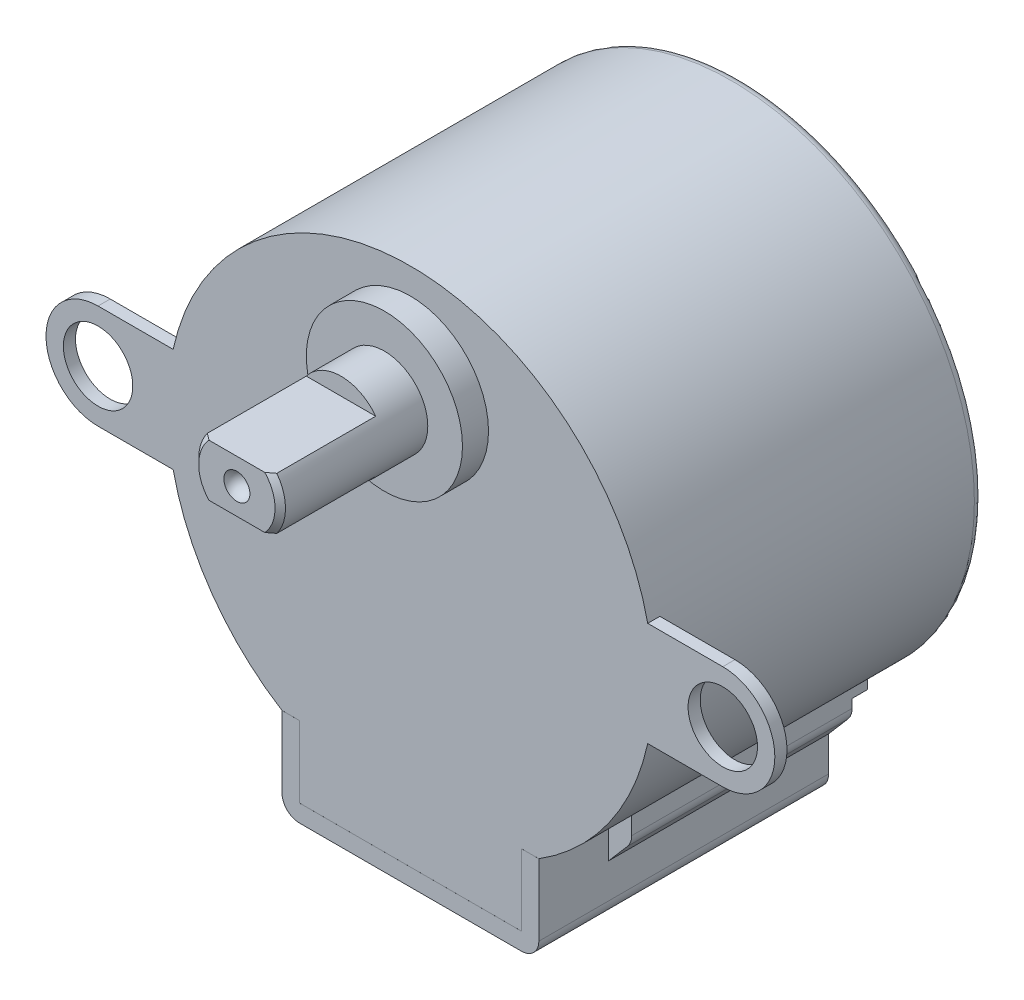
SolidWorks part; units mm, degrees
ref_plane "Ön Düzlem" through (0, 0, 0) normal (0, 0, 1) x (1, 0, 0)
ref_plane "Üst Düzlem" through (0, 0, 0) normal (0, 1, 0) x (1, 0, 0)
ref_plane "Sağ Düzlem" through (0, 0, 0) normal (1, 0, 0) x (0, 0, -1)
sketch "Çizim1" plane through (0, 0, 0) normal (0, 0, 1) x (1, 0, 0)
  circle A0 centre (0, 0) radius 14
  dimension "D1" = 28
extrude "Yükseklik-Ekstrüzyon1" add sketch "Çizim1" along normal blind 19
sketch "Çizim2" plane through (0, 0, 19) normal (0, 0, 1) x (1, 0, 0)
  line L0 (0, 14) -> (0, 8) construction
  circle A0 centre (0, 0) radius 14 construction
  circle A1 centre (0, 8) radius 4.5
  dimension "D2" = 9
  dimension "D1" = 6
extrude "Yükseklik-Ekstrüzyon2" add sketch "Çizim2" along normal blind 1.5
sketch "Çizim3" plane through (0, 0, 20.5) normal (0, 0, 1) x (1, 0, 0)
  circle A0 centre (0, 8) radius 2.5
  dimension "D1" = 5
extrude "Yükseklik-Ekstrüzyon3" add sketch "Çizim3" along normal blind 8.5
sketch "Çizim4" plane through (0, 0, 29) normal (0, 0, 1) x (1, 0, 0)
  line L0 (0, 10.5) -> (0, 9.5) construction
  line L1 (0, 9.5) -> (2.1768, 9.5)
  line L2 (2.1768, 9.5) -> (2.1768, 10.5)
  line L3 (2.1768, 10.5) -> (-2.3997, 10.5)
  line L4 (-2.3997, 10.5) -> (-2.3997, 9.5)
  line L5 (-2.3997, 9.5) -> (0, 9.5)
  line L6 (0, 8) -> (1.2994, 8) construction
  line L7 (2.1768, 5.5) -> (-2.3997, 5.5)
  line L8 (2.1768, 6.5) -> (2.1768, 5.5)
  line L9 (-2.3997, 5.5) -> (-2.3997, 6.5)
  line L10 (-2.3997, 6.5) -> (0, 6.5)
  line L11 (0, 6.5) -> (2.1768, 6.5)
  circle A0 centre (0, 8) radius 2.5 construction
  circle A1 centre (0, 8) radius 2.5 construction
  dimension "D1" = 1
extrude "Kes-Ekstrüzyon1" cut sketch "Çizim4" against normal blind 6
chamfer "Pah1" distance 0.3 angle 45 2 edges at (-2.5, 8, 29) (2.5, 8, 29)
sketch "Çizim5" plane through (0, 0, 29) normal (0, 0, 1) x (1, 0, 0)
  line L0 (0, 8.75) -> (0, 7.25) construction
  line L1 (0, 8.75) -> (0, 7.25)
  arc A0 (0, 7.25) -> (0, 8.75) centre (0, 8) ccw
  dimension "D1" = 1.5
revolve "Kes-Döndür1" cut sketch "Çizim5" angle 360 about L0
sketch "Çizim6" plane through (0, 0, 19) normal (0, 0, 1) x (1, 0, 0)
  line L0 (0, 0) -> (0, -17) construction
  line L1 (0, -17) -> (7.4, -17)
  line L2 (7.4, -17) -> (7.4, -11.8844)
  line L4 (-7.4, -11.8844) -> (-7.4, -17)
  line L5 (-7.4, -17) -> (0, -17)
  arc A0 (-7.4, -11.8844) -> (7.4, -11.8844) centre (0, 0) ccw
  dimension "D1" = 17
  dimension "D2" = 7.4
  dimension "D3" = 7.4
extrude "Yükseklik-Ekstrüzyon4" add sketch "Çizim6" against normal blind 16.7
fillet "Radyus2" radius 1 2 edges at (7.4, -17, 10.65) (-7.4, -17, 10.65)
sketch "Çizim7" plane through (0, 0, 2.3) normal (0, 0, -1) x (-1, 0, 0)
  line L0 (7.4, -14) -> (7.4, -10.9287)
  line L1 (7.4, -11.8844) -> (7.4, -16) construction
  line L2 (7.4, -14) -> (8.75, -14) construction
  line L3 (8.75, -10.9287) -> (8.75, -12.0582)
  line L4 (7.4, -14) -> (8.5085, -12.7098)
  line L5 (7.4, -10.9287) -> (8.75, -10.9287)
  line L6 (0, -17) -> (0, -15.0954) construction
  line L7 (6.4, -17) -> (-6.4, -17) construction
  line L8 (-7.4, -14) -> (-7.4, -10.9287)
  line L9 (-7.4, -10.9287) -> (-8.75, -10.9287)
  line L10 (-8.75, -10.9287) -> (-8.75, -12.0582)
  line L11 (-7.4, -14) -> (-8.5085, -12.7098)
  circle A1 centre (0, 0) radius 14 construction
  arc A2 (8.75, -12.0582) -> (8.5085, -12.7098) centre (7.75, -12.0582) cw
  arc A3 (-8.75, -12.0582) -> (-8.5085, -12.7098) centre (-7.75, -12.0582) ccw
  point P21 (8.75, -12.4287)
  point P24 (-8.75, -12.4287)
  dimension "D1" = 1
  dimension "D2" = 1.35
  dimension "D3" = 1.5
extrude "Yükseklik-Ekstrüzyon5" add sketch "Çizim7" against normal blind 12.7
sketch "Çizim8" plane through (0, 0, 2.3) normal (0, 0, -1) x (-1, 0, 0)
  line L0 (-8.75, -10.9287) -> (-8.75, -11.5623)
  line L1 (8.75, -10.9287) -> (8.75, -11.5623)
  line L4 (1.5, -14.4222) -> (1.5, -13.9194)
  line L5 (-1.5, -14.4222) -> (-1.5, -13.9194)
  arc A0 (-8.75, -11.5623) -> (-1.5, -14.4222) centre (0, 0) ccw
  arc A1 (-8.75, -10.9287) -> (-1.5, -13.9194) centre (0, 0) ccw
  arc A2 (1.5, -13.9194) -> (8.75, -10.9287) centre (0, 0) ccw
  arc A3 (1.5, -14.4222) -> (8.75, -11.5623) centre (0, 0) ccw
  dimension "D1" = 29
extrude "Yükseklik-Ekstrüzyon6" add sketch "Çizim8" along normal blind 0.9
sketch "Çizim9" plane through (0, -17, 0) normal (0, -1, 0) x (1, 0, 0)
  line L0 (0, 19) -> (0, 17) construction
  line L1 (-6.4, 19) -> (6.4, 19) construction
  line L2 (0, 17) -> (3.2, 17) construction
  line L3 (3.2, 17) -> (3.2, 16) construction
  line L4 (3.2, 17) -> (-3.2, 17)
  line L6 (-3.2, 16) -> (3.2, 16)
  arc A0 (3.2, 16) -> (3.2, 17) centre (3.2, 16.5) ccw
  arc A1 (-3.2, 17) -> (-3.2, 16) centre (-3.2, 16.5) ccw
  dimension "D1" = 2
  dimension "D2" = 3.2
  dimension "D3" = 1
  dimension "D4" = 6.4
  dimension "D5" = 6.4
extrude "Kes-Ekstrüzyon2" cut sketch "Çizim9" against normal blind 2.3
fillet "Radyus3" radius 0.5 1 edges at (14, 0, 0)
sketch "Çizim10" plane through (0, 0, 19) normal (0, 0, 1) x (1, 0, 0)
  line L0 (0, 0) -> (0, -3) construction
  line L1 (0, -3) -> (18, -3) construction
  line L2 (18, 3) -> (13.6748, 3)
  line L3 (18, -3) -> (13.6748, -3)
  line L4 (-18, -3) -> (-13.6748, -3)
  line L5 (-18, 3) -> (-13.6748, 3)
  arc A0 (18, -3) -> (18, 3) centre (18, 0) ccw
  circle A1 centre (18, 0) radius 2
  arc A2 (7.4, -11.8844) -> (-7.4, -11.8844) centre (0, 0) ccw construction
  arc A3 (13.6748, -3) -> (13.6748, 3) centre (0, 0) ccw
  arc A4 (-13.6748, -3) -> (-13.6748, 3) centre (0, 0) cw
  circle A5 centre (-18, 0) radius 2
  arc A6 (-18, -3) -> (-18, 3) centre (-18, 0) cw
  dimension "D3" = 4
  dimension "D1" = 3
  dimension "D2" = 18
extrude "Yükseklik-Ekstrüzyon7" add sketch "Çizim10" against normal blind 0.7
sketch "Çizim11" plane through (0, 0, 0) normal (0, 0, -1) x (-1, 0, 0)
  text T0 "28BYJ-48"
extrude "Kes-Ekstrüzyon3" cut sketch "Çizim11" against normal blind 0.3
sketch "Çizim12" plane through (0, 0, 19) normal (0, 0, 1) x (1, 0, 0)
  line L0 (-7.4, -11.8844) -> (-6.4, -11.8844)
  line L1 (-6.4, -11.8844) -> (-6.4, -16)
  line L2 (-6.4, -16) -> (6.4, -16)
  line L3 (6.4, -16) -> (6.4, -11.8844)
  line L4 (6.4, -11.8844) -> (7.4, -11.8844)
  line L5 (7.4, -11.8844) -> (7.4, -16)
  line L6 (6.4, -17) -> (-6.4, -17)
  line L7 (-7.4, -16) -> (-7.4, -11.8844)
  arc A0 (6.4, -17) -> (7.4, -16) centre (6.4, -16) ccw construction
  arc A1 (7.4, -16) -> (6.4, -17) centre (6.4, -16) cw
  arc A2 (-6.4, -17) -> (-7.4, -16) centre (-6.4, -16) cw
extrude "Yükseklik-Ekstrüzyon8" add sketch "Çizim12" along normal blind 0.001
